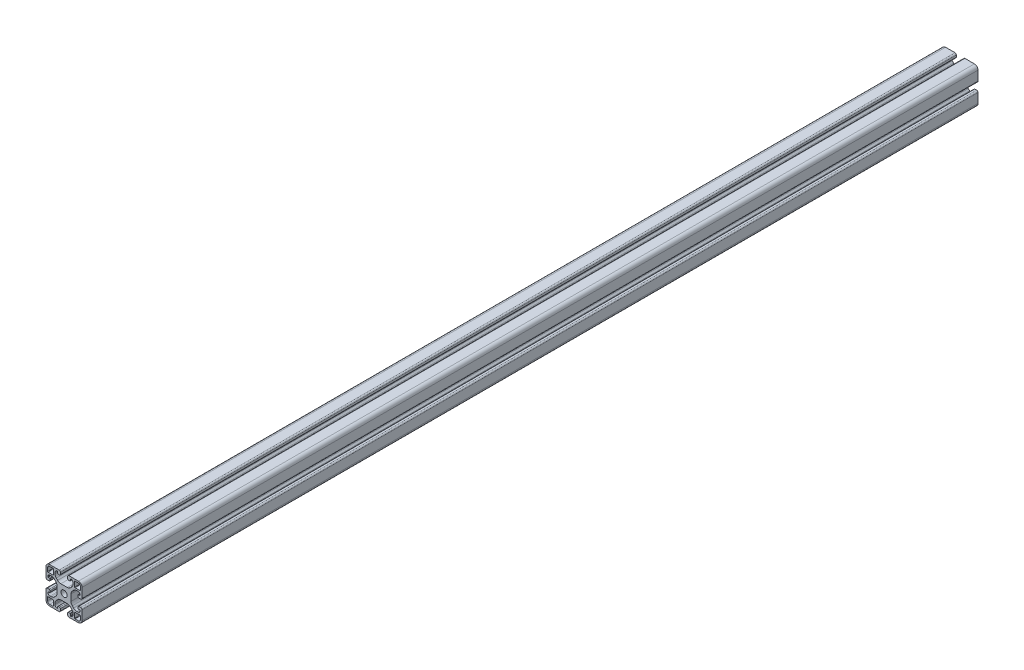
SolidWorks part; units mm, degrees
ref_plane "Plan de face" through (0, 0, 0) normal (0, 0, 1) x (1, 0, 0)
ref_plane "Plan de dessus" through (0, 0, 0) normal (0, 1, 0) x (1, 0, 0)
ref_plane "Plan de droite" through (0, 0, 0) normal (1, 0, 0) x (0, 0, -1)
ref_plane "Plan1" through (0, 0, -30) normal (0, 0, -1) x (-1, 0, 0)
sketch "Esquisse1" plane through (0, 0, -30) normal (0, 0, -1) x (-1, 0, 0)
  line L0 (-4.5, 15) -> (-4.5, 13.5)
  line L1 (-4, 13) -> (-2.5, 13)
  line L2 (-4.5, 10) -> (-5.8076, 10)
  line L3 (-9.3431, 11.4645) -> (-10.7855, 12.9069)
  line L4 (-12.25, 16.4424) -> (-12.25, 23.5576)
  line L5 (-10.7855, 27.0931) -> (-9.3431, 28.5355)
  line L6 (-5.8076, 30) -> (-4.5, 30)
  line L7 (-2.5, 27) -> (-4, 27)
  line L8 (-4.5, 26.5) -> (-4.5, 25)
  line L9 (-3.5, 24) -> (-1.5, 24)
  line L10 (0, 25.5) -> (0, 36)
  line L11 (-4, 40) -> (-14.5, 40)
  line L12 (-16, 38.5) -> (-16, 36.5)
  line L13 (-15, 35.5) -> (-13.5, 35.5)
  line L14 (-13, 36) -> (-13, 37.5)
  line L15 (-10, 35.5) -> (-10, 34.1924)
  line L16 (-11.4645, 30.6569) -> (-12.9069, 29.2145)
  line L17 (-16.4424, 27.75) -> (-23.5576, 27.75)
  line L18 (-27.0931, 29.2145) -> (-28.5355, 30.6569)
  line L19 (-30, 34.1924) -> (-30, 35.5)
  line L20 (-27, 37.5) -> (-27, 36)
  line L21 (-26.5, 35.5) -> (-25, 35.5)
  line L22 (-24, 36.5) -> (-24, 38.5)
  line L23 (-25.5, 40) -> (-36, 40)
  line L24 (-40, 36) -> (-40, 25.5)
  line L25 (-38.5, 24) -> (-36.5, 24)
  line L26 (-35.5, 25) -> (-35.5, 26.5)
  line L27 (-36, 27) -> (-37.5, 27)
  line L28 (-35.5, 30) -> (-34.1924, 30)
  line L29 (-30.6569, 28.5355) -> (-29.2145, 27.0931)
  line L30 (-27.75, 23.5576) -> (-27.75, 16.4424)
  line L31 (-29.2145, 12.9069) -> (-30.6569, 11.4645)
  line L32 (-34.1924, 10) -> (-35.5, 10)
  line L33 (-37.5, 13) -> (-36, 13)
  line L34 (-35.5, 13.5) -> (-35.5, 15)
  line L35 (-36.5, 16) -> (-38.5, 16)
  line L36 (-40, 14.5) -> (-40, 4)
  line L37 (-36, 0) -> (-25.5, 0)
  line L38 (-24, 1.5) -> (-24, 3.5)
  line L39 (-25, 4.5) -> (-26.5, 4.5)
  line L40 (-27, 4) -> (-27, 2.5)
  line L41 (-30, 4.5) -> (-30, 5.8076)
  line L42 (-28.5355, 9.3431) -> (-27.0931, 10.7855)
  line L43 (-23.5576, 12.25) -> (-16.4424, 12.25)
  line L44 (-12.9069, 10.7855) -> (-11.4645, 9.3431)
  line L45 (-10, 5.8076) -> (-10, 4.5)
  line L46 (-13, 2.5) -> (-13, 4)
  line L47 (-13.5, 4.5) -> (-15, 4.5)
  line L48 (-16, 3.5) -> (-16, 1.5)
  line L49 (-14.5, 0) -> (-4, 0)
  line L50 (0, 4) -> (0, 14.5)
  line L51 (-1.5, 16) -> (-3.5, 16)
  line L52 (-4, 1.8) -> (-7.7, 1.8)
  line L53 (-8.2, 2.3) -> (-8.2, 7.7)
  line L54 (-7.7, 8.2) -> (-2.3, 8.2)
  line L55 (-1.8, 7.7) -> (-1.8, 4)
  line L56 (-38.2, 4) -> (-38.2, 7.7)
  line L57 (-37.7, 8.2) -> (-32.3, 8.2)
  line L58 (-31.8, 7.7) -> (-31.8, 2.3)
  line L59 (-32.3, 1.8) -> (-36, 1.8)
  line L60 (-36, 38.2) -> (-32.3, 38.2)
  line L61 (-31.8, 37.7) -> (-31.8, 32.3)
  line L62 (-32.3, 31.8) -> (-37.7, 31.8)
  line L63 (-38.2, 32.3) -> (-38.2, 36)
  line L64 (-1.8, 36) -> (-1.8, 32.3)
  line L65 (-2.3, 31.8) -> (-7.7, 31.8)
  line L66 (-8.2, 32.3) -> (-8.2, 37.7)
  line L67 (-7.7, 38.2) -> (-4, 38.2)
  arc A0 (-4.5, 13.5) -> (-4, 13) centre (-4, 13.5) ccw
  arc A1 (-2.5, 13) -> (-2, 12.5) centre (-2.5, 12.5) cw
  arc A2 (-2, 12.5) -> (-4.5, 10) centre (-4.5, 12.5) cw
  arc A3 (-5.8076, 10) -> (-9.3431, 11.4645) centre (-5.8076, 15) cw
  arc A4 (-10.7855, 12.9069) -> (-12.25, 16.4424) centre (-7.25, 16.4424) cw
  arc A5 (-12.25, 23.5576) -> (-10.7855, 27.0931) centre (-7.25, 23.5576) cw
  arc A6 (-9.3431, 28.5355) -> (-5.8076, 30) centre (-5.8076, 25) cw
  arc A7 (-4.5, 30) -> (-2, 27.5) centre (-4.5, 27.5) cw
  arc A8 (-2, 27.5) -> (-2.5, 27) centre (-2.5, 27.5) cw
  arc A9 (-4, 27) -> (-4.5, 26.5) centre (-4, 26.5) ccw
  arc A10 (-4.5, 25) -> (-3.5, 24) centre (-3.5, 25) ccw
  arc A11 (-1.5, 24) -> (0, 25.5) centre (-1.5, 25.5) ccw
  arc A12 (0, 36) -> (-4, 40) centre (-4, 36) ccw
  arc A13 (-14.5, 40) -> (-16, 38.5) centre (-14.5, 38.5) ccw
  arc A14 (-16, 36.5) -> (-15, 35.5) centre (-15, 36.5) ccw
  arc A15 (-13.5, 35.5) -> (-13, 36) centre (-13.5, 36) ccw
  arc A16 (-13, 37.5) -> (-12.5, 38) centre (-12.5, 37.5) cw
  arc A17 (-12.5, 38) -> (-10, 35.5) centre (-12.5, 35.5) cw
  arc A18 (-10, 34.1924) -> (-11.4645, 30.6569) centre (-15, 34.1924) cw
  arc A19 (-12.9069, 29.2145) -> (-16.4424, 27.75) centre (-16.4424, 32.75) cw
  arc A20 (-23.5576, 27.75) -> (-27.0931, 29.2145) centre (-23.5576, 32.75) cw
  arc A21 (-28.5355, 30.6569) -> (-30, 34.1924) centre (-25, 34.1924) cw
  arc A22 (-30, 35.5) -> (-27.5, 38) centre (-27.5, 35.5) cw
  arc A23 (-27.5, 38) -> (-27, 37.5) centre (-27.5, 37.5) cw
  arc A24 (-27, 36) -> (-26.5, 35.5) centre (-26.5, 36) ccw
  arc A25 (-25, 35.5) -> (-24, 36.5) centre (-25, 36.5) ccw
  arc A26 (-24, 38.5) -> (-25.5, 40) centre (-25.5, 38.5) ccw
  arc A27 (-36, 40) -> (-40, 36) centre (-36, 36) ccw
  arc A28 (-40, 25.5) -> (-38.5, 24) centre (-38.5, 25.5) ccw
  arc A29 (-36.5, 24) -> (-35.5, 25) centre (-36.5, 25) ccw
  arc A30 (-35.5, 26.5) -> (-36, 27) centre (-36, 26.5) ccw
  arc A31 (-37.5, 27) -> (-38, 27.5) centre (-37.5, 27.5) cw
  arc A32 (-38, 27.5) -> (-35.5, 30) centre (-35.5, 27.5) cw
  arc A33 (-34.1924, 30) -> (-30.6569, 28.5355) centre (-34.1924, 25) cw
  arc A34 (-29.2145, 27.0931) -> (-27.75, 23.5576) centre (-32.75, 23.5576) cw
  arc A35 (-27.75, 16.4424) -> (-29.2145, 12.9069) centre (-32.75, 16.4424) cw
  arc A36 (-30.6569, 11.4645) -> (-34.1924, 10) centre (-34.1924, 15) cw
  arc A37 (-35.5, 10) -> (-38, 12.5) centre (-35.5, 12.5) cw
  arc A38 (-38, 12.5) -> (-37.5, 13) centre (-37.5, 12.5) cw
  arc A39 (-36, 13) -> (-35.5, 13.5) centre (-36, 13.5) ccw
  arc A40 (-35.5, 15) -> (-36.5, 16) centre (-36.5, 15) ccw
  arc A41 (-38.5, 16) -> (-40, 14.5) centre (-38.5, 14.5) ccw
  arc A42 (-40, 4) -> (-36, 0) centre (-36, 4) ccw
  arc A43 (-25.5, 0) -> (-24, 1.5) centre (-25.5, 1.5) ccw
  arc A44 (-24, 3.5) -> (-25, 4.5) centre (-25, 3.5) ccw
  arc A45 (-26.5, 4.5) -> (-27, 4) centre (-26.5, 4) ccw
  arc A46 (-27, 2.5) -> (-27.5, 2) centre (-27.5, 2.5) cw
  arc A47 (-27.5, 2) -> (-30, 4.5) centre (-27.5, 4.5) cw
  arc A48 (-30, 5.8076) -> (-28.5355, 9.3431) centre (-25, 5.8076) cw
  arc A49 (-27.0931, 10.7855) -> (-23.5576, 12.25) centre (-23.5576, 7.25) cw
  arc A50 (-16.4424, 12.25) -> (-12.9069, 10.7855) centre (-16.4424, 7.25) cw
  arc A51 (-11.4645, 9.3431) -> (-10, 5.8076) centre (-15, 5.8076) cw
  arc A52 (-10, 4.5) -> (-12.5, 2) centre (-12.5, 4.5) cw
  arc A53 (-12.5, 2) -> (-13, 2.5) centre (-12.5, 2.5) cw
  arc A54 (-13, 4) -> (-13.5, 4.5) centre (-13.5, 4) ccw
  arc A55 (-15, 4.5) -> (-16, 3.5) centre (-15, 3.5) ccw
  arc A56 (-16, 1.5) -> (-14.5, 0) centre (-14.5, 1.5) ccw
  arc A57 (-4, 0) -> (0, 4) centre (-4, 4) ccw
  arc A58 (0, 14.5) -> (-1.5, 16) centre (-1.5, 14.5) ccw
  arc A59 (-3.5, 16) -> (-4.5, 15) centre (-3.5, 15) ccw
  circle A60 centre (-20, 20) radius 3.4
  arc A61 (-1.8, 4) -> (-4, 1.8) centre (-4, 4) cw
  arc A62 (-7.7, 1.8) -> (-8.2, 2.3) centre (-7.7, 2.3) cw
  arc A63 (-8.2, 7.7) -> (-7.7, 8.2) centre (-7.7, 7.7) cw
  arc A64 (-2.3, 8.2) -> (-1.8, 7.7) centre (-2.3, 7.7) cw
  arc A65 (-36, 1.8) -> (-38.2, 4) centre (-36, 4) cw
  arc A66 (-38.2, 7.7) -> (-37.7, 8.2) centre (-37.7, 7.7) cw
  arc A67 (-32.3, 8.2) -> (-31.8, 7.7) centre (-32.3, 7.7) cw
  arc A68 (-31.8, 2.3) -> (-32.3, 1.8) centre (-32.3, 2.3) cw
  arc A69 (-38.2, 36) -> (-36, 38.2) centre (-36, 36) cw
  arc A70 (-32.3, 38.2) -> (-31.8, 37.7) centre (-32.3, 37.7) cw
  arc A71 (-31.8, 32.3) -> (-32.3, 31.8) centre (-32.3, 32.3) cw
  arc A72 (-37.7, 31.8) -> (-38.2, 32.3) centre (-37.7, 32.3) cw
  arc A73 (-4, 38.2) -> (-1.8, 36) centre (-4, 36) cw
  arc A74 (-1.8, 32.3) -> (-2.3, 31.8) centre (-2.3, 32.3) cw
  arc A75 (-7.7, 31.8) -> (-8.2, 32.3) centre (-7.7, 32.3) cw
  arc A76 (-8.2, 37.7) -> (-7.7, 38.2) centre (-7.7, 37.7) cw
extrude "Boss.-Extru.1" add sketch "Esquisse1" against normal blind 995
